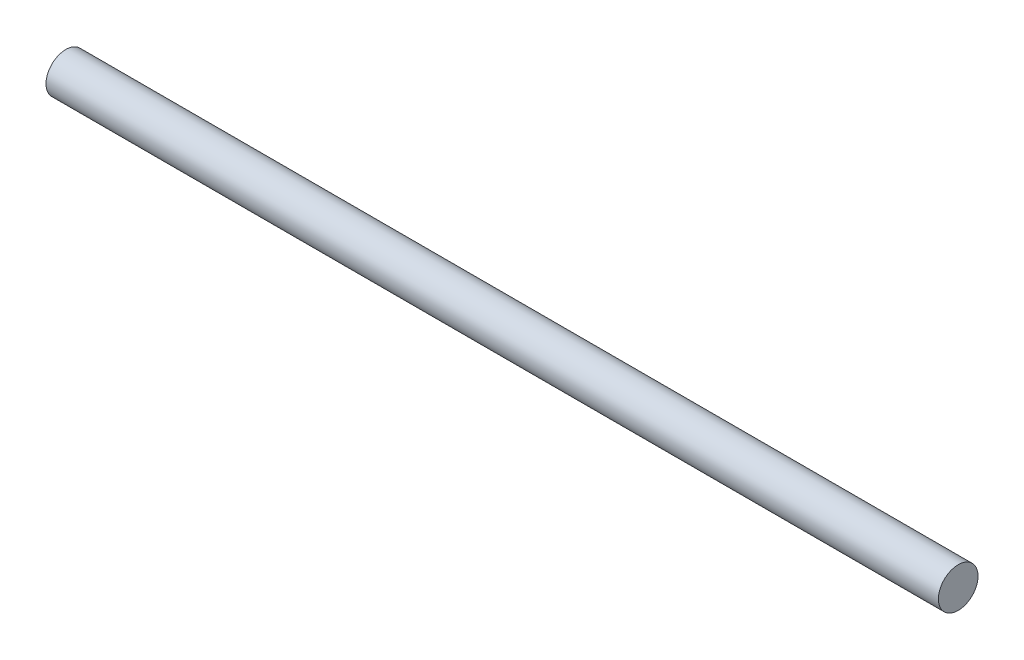
SolidWorks part; units mm, degrees
ref_plane "Front Plane" through (0, 0, 0) normal (0, 0, 1) x (1, 0, 0)
ref_plane "Top Plane" through (0, 0, 0) normal (0, 1, 0) x (1, 0, 0)
ref_plane "Right Plane" through (0, 0, 0) normal (1, 0, 0) x (0, 0, -1)
sketch "Sketch1" plane through (0, 0, 0) normal (1, 0, 0) x (0, 0, -1)
  circle A0 centre (0, 0) radius 2
  dimension "D1" = 4
extrude "Boss-Extrude1" add sketch "Sketch1" along normal blind 90
